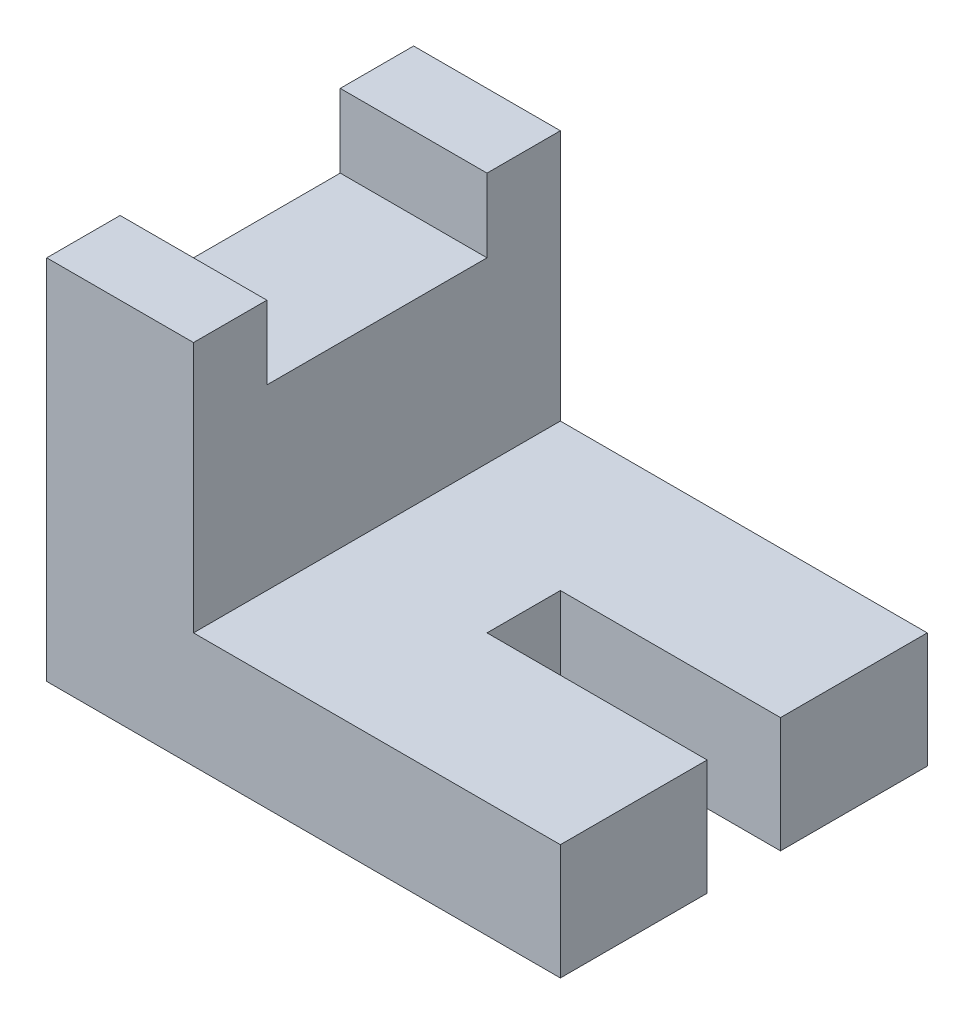
SolidWorks part; units mm, degrees
ref_plane "Front Plane" through (0, 0, 0) normal (0, 0, 1) x (1, 0, 0)
ref_plane "Top Plane" through (0, 0, 0) normal (0, 1, 0) x (1, 0, 0)
ref_plane "Right Plane" through (0, 0, 0) normal (1, 0, 0) x (0, 0, -1)
sketch "Sketch2" plane through (0, 0, 0) normal (0, 0, 1) x (1, 0, 0)
  line L0 (-18.2284, 0) -> (26.2216, 0)
  line L1 (26.2216, 0) -> (26.2216, 9.9915)
  line L2 (26.2216, 9.9915) -> (-5.5284, 9.9915)
  line L3 (-5.5284, 9.9915) -> (-5.5284, 31.75)
  line L4 (-5.5284, 31.75) -> (-18.2284, 31.75)
  line L5 (-18.2284, 31.75) -> (-18.2284, 0)
  dimension "D1" = 44.45
  dimension "D2" = 31.75
  dimension "D3" = 31.75
extrude "Boss-Extrude1" add sketch "Sketch2" against normal blind 31.75
sketch "Sketch3" plane through (0, 31.75, 0) normal (0, 1, 0) x (1, 0, 0)
  line L0 (-18.2284, 31.75) -> (-18.2284, 0) construction
  line L1 (-18.2284, 6.35) -> (-5.5284, 6.35)
  line L2 (-18.2284, 6.35) -> (-18.2284, 25.4)
  line L3 (-18.2284, 25.4) -> (-5.5284, 25.4)
  line L4 (-5.5284, 6.35) -> (-5.5284, 25.4)
  line L5 (-5.5284, 31.75) -> (-5.5284, 0) construction
  line L6 (-18.2284, 6.35) -> (-18.2284, 0)
  line M7 (-5.5284, 0) -> (-5.5284, 31.75)
  line M9 (-18.2284, 31.75) -> (-18.2284, 0)
  dimension "D1" = 19.05
  dimension "D2" = 6.35
extrude "Cut-Extrude1" cut sketch "Sketch3" against normal blind 6.35 contours L3 L1 M9 M7
sketch "Sketch4" plane through (0, 9.9915, 0) normal (0, 1, 0) x (1, 0, 0)
  line L0 (26.2216, 31.75) -> (26.2216, 0) construction
  line L1 (26.2216, 19.05) -> (7.1716, 19.05)
  line L2 (26.2216, 19.05) -> (26.2216, 12.7)
  line L3 (26.2216, 12.7) -> (7.1716, 12.7)
  line L4 (7.1716, 19.05) -> (7.1716, 12.7)
  line L5 (-5.5284, 31.75) -> (-5.5284, 0) construction
  dimension "D1" = 12.7
  dimension "D2" = 6.35
  dimension "D3" = 12.7
extrude "Cut-Extrude2" cut sketch "Sketch4" against normal through all
